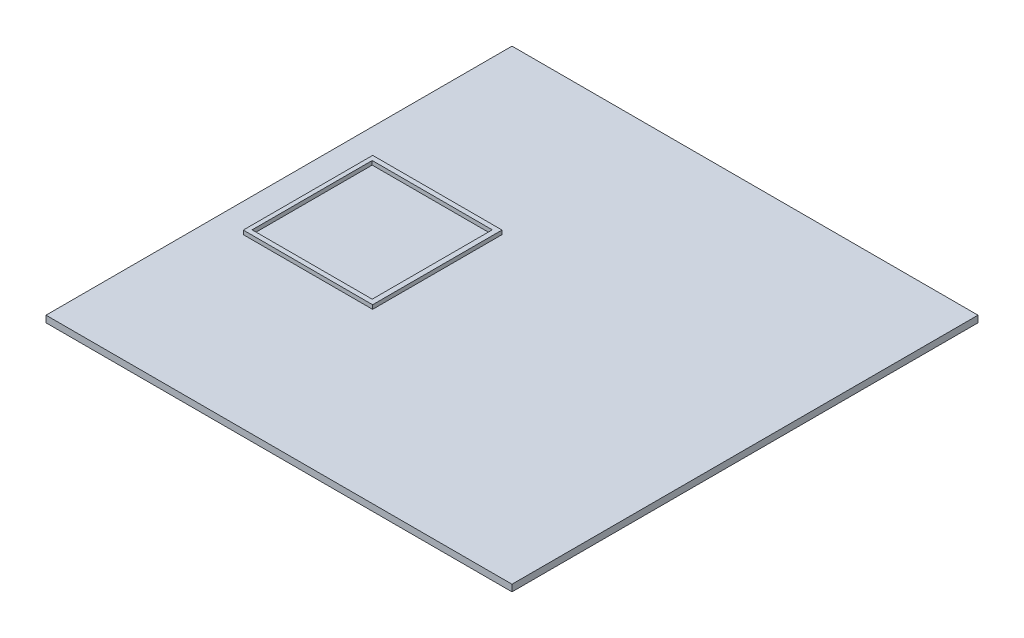
SolidWorks part; units mm, degrees
ref_plane "Front Plane" through (0, 0, 0) normal (0, 0, 1) x (1, 0, 0)
ref_plane "Top Plane" through (0, 0, 0) normal (0, 1, 0) x (1, 0, 0)
ref_plane "Right Plane" through (0, 0, 0) normal (1, 0, 0) x (0, 0, -1)
sketch "Sketch2" plane through (0, 0, 0) normal (0, 1, 0) x (1, 0, 0)
  line L1 (-175, 175) -> (175, 175)
  line L2 (-175, 175) -> (-175, -175)
  line L3 (-175, -175) -> (175, -175)
  line L4 (175, 175) -> (175, -175)
  line L5 (-175, 175) -> (175, -175) construction
  line L6 (-175, -175) -> (175, 175) construction
  point P0 (0, 0)
  dimension "D1" = 350
extrude "Boss-Extrude1" add sketch "Sketch2" along normal blind 5
sketch "Sketch4" plane through (0, 5, 0) normal (0, 1, 0) x (1, 0, 0)
  line L0 (-105, 0) -> (0, 0) construction
  line L1 (-56.1212, 45.1) -> (-56.1212, 48.6228)
  line L7 (-150.1, 45.1) -> (-59.9, -45.1) construction
  line L8 (-150.1, -45.1) -> (-59.9, 45.1) construction
  line L10 (-150.1, 48.6228) -> (-59.9, 48.6228)
  line L15 (-153.2649, 45.1) -> (-153.2649, -45.1)
  line L18 (-150.1, -48.5575) -> (-59.9, -48.5575)
  line L23 (-56.1212, -45.1) -> (-56.1212, 45.1)
  line L25 (-153.2649, -45.1) -> (-153.2649, -48.5575)
  line L26 (-153.2649, -48.5575) -> (-150.1, -48.5575)
  line L29 (-153.2649, 45.1) -> (-153.2649, 48.6228)
  line L30 (-153.2649, 48.6228) -> (-150.1, 48.6228)
  line L34 (-56.1212, 48.6228) -> (-59.9, 48.6228)
  line L36 (-59.9, -48.5575) -> (-56.1212, -48.5575)
  line L39 (-56.1212, -48.5575) -> (-56.1212, -45.1)
  line L41 (-150.1, 45.1) -> (-59.9, 45.1)
  line L42 (-150.1, 45.1) -> (-150.1, -45.1)
  line L43 (-150.1, -45.1) -> (-59.9, -45.1)
  line L44 (-59.9, 45.1) -> (-59.9, -45.1)
  circle A0 centre (-105, 0) radius 20 construction
  dimension "D1" = 40
  dimension "D3" = 90.2
extrude "Boss-Extrude2" add sketch "Sketch4" along normal blind 3
